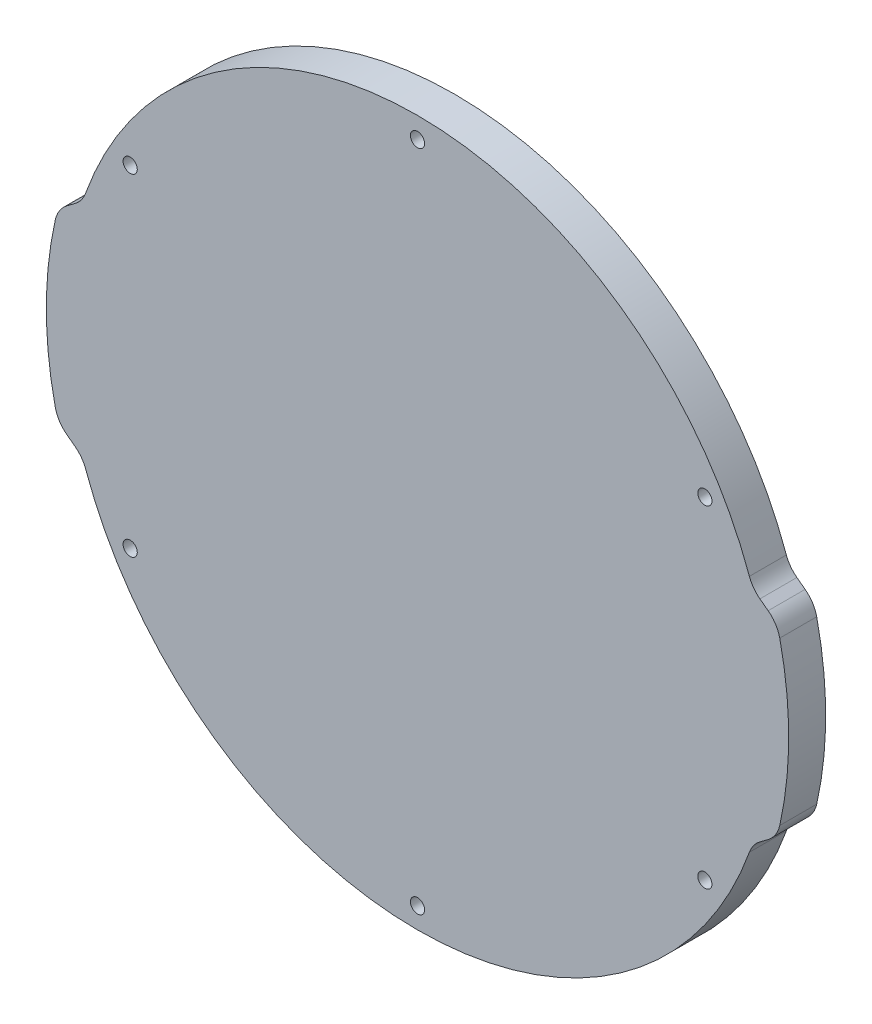
SolidWorks part; units mm, degrees
ref_plane "Plan de face" through (0, 0, 0) normal (0, 0, 1) x (1, 0, 0)
ref_plane "Plan de dessus" through (0, 0, 0) normal (0, 1, 0) x (1, 0, 0)
ref_plane "Plan de droite" through (0, 0, 0) normal (1, 0, 0) x (0, 0, -1)
sketch "Esquisse1" plane through (0, 0, 0) normal (0, 0, 1) x (1, 0, 0)
  line L0 (-86.1821, 18) -> (83.9395, 18) construction
  line L1 (83.9395, 0) -> (-86.1821, 0) construction
  line L2 (-86.1821, -18) -> (83.9395, -18) construction
  line L3 (-86.1821, 15) -> (83.9395, 15) construction
  line L4 (83.9395, -15) -> (-86.1821, -15) construction
  line L5 (-58.3529, 15) -> (-54.3467, 18)
  line L6 (-58.3529, -15) -> (-54.3467, -18)
  line L7 (54.3467, -18) -> (58.3529, -15)
  line L8 (58.3529, 15) -> (54.3467, 18)
  line L9 (0, 0) -> (0, 69.3457) construction
  circle A0 centre (0, 0) radius 57.25 construction
  circle A1 centre (0, 0) radius 60.25 construction
  arc A2 (-54.3467, 18) -> (54.3467, 18) centre (0, 0) cw
  arc A3 (-54.3467, -18) -> (54.3467, -18) centre (0, 0) ccw
  arc A4 (-58.3529, 15) -> (-58.3529, -15) centre (0, 0) ccw
  arc A5 (58.3529, 15) -> (58.3529, -15) centre (0, 0) cw
  circle A6 centre (0, 53.85) radius 1.15
  circle A7 centre (46.6355, 26.925) radius 1.15
  circle A8 centre (46.6355, -26.925) radius 1.15
  circle A9 centre (0, -53.85) radius 1.15
  circle A10 centre (-46.6355, -26.925) radius 1.15
  circle A11 centre (-46.6355, 26.925) radius 1.15
  point P42 (0, 0)
  dimension "D1" = 114.5
  dimension "D2" = 120.5
  dimension "D6" = 2.3
  dimension "D3" = 36
  dimension "D4" = 30
  dimension "D5" = 53.85
  dimension "D7" = 6
extrude "Boss.-Extru.1" add sketch "Esquisse1" along normal blind 6
fillet "Congé1" radius 5 8 edges at (-54.3467, 18, 3) (-58.3529, 15, 3) (-58.3529, -15, 3) (-54.3467, -18, 3) (54.3467, -18, 3) (58.3529, -15, 3) (58.3529, 15, 3) (54.3467, 18, 3)
